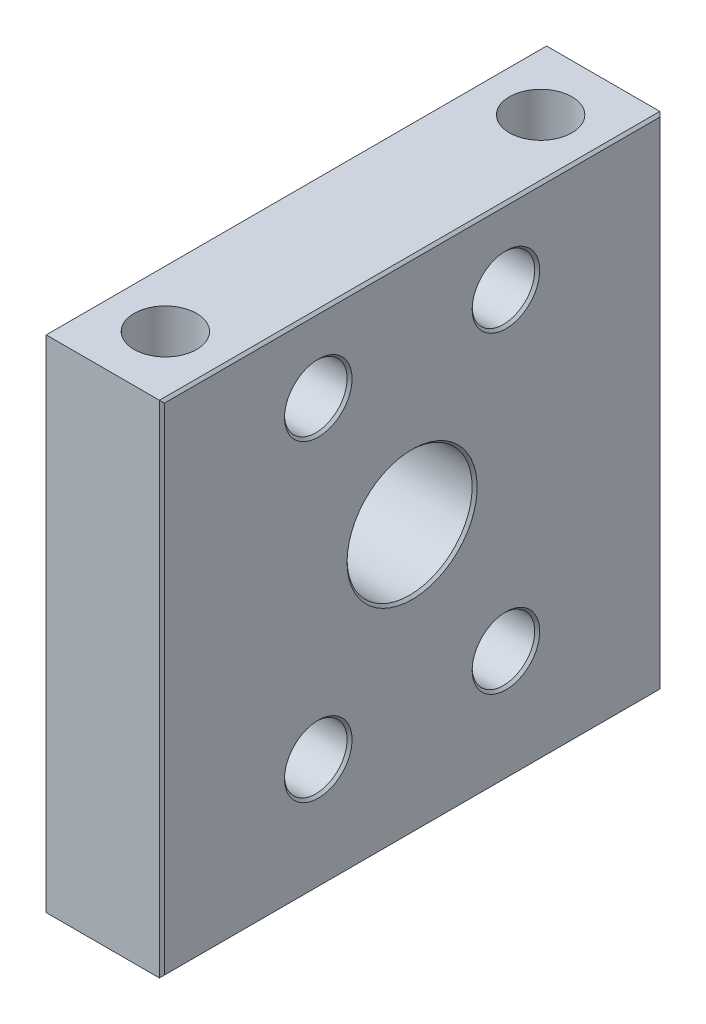
SolidWorks part; units mm, degrees
material "1060 Alloy"
ref_plane "Front Plane" through (0, 0, 0) normal (0, 0, 1) x (1, 0, 0)
ref_plane "Top Plane" through (0, 0, 0) normal (0, 1, 0) x (1, 0, 0)
ref_plane "Right Plane" through (0, 0, 0) normal (1, 0, 0) x (0, 0, -1)
sketch "Sketch1" plane through (0, 0, 0) normal (0, 1, 0) x (1, 0, 0)
  line L1 (6.001, -25.4) -> (-6.001, -25.4)
  line L2 (6.001, -25.4) -> (6.001, 25.4)
  line L3 (6.001, 25.4) -> (-6.001, 25.4)
  line L4 (-6.001, -25.4) -> (-6.001, 25.4)
  line L5 (6.001, -25.4) -> (-6.001, 25.4) construction
  line L6 (6.001, 25.4) -> (-6.001, -25.4) construction
  circle A0 centre (0, 19.05) radius 3.175
  circle A1 centre (0, -19.05) radius 3.175
  point P0 (0, 0)
  dimension "D1" = 6.35
  dimension "D3" = 6.35
  dimension "D2" = 50.8
  dimension "D4" = 38.1
  dimension "D5" = 6.35
extrude "Boss-Extrude1" add sketch "Sketch1" along normal blind 50.8
sketch "Sketch2" plane through (6.001, 0, 0) normal (1, 0, 0) x (0, 0, -1)
  line L15 (-9.525, 43.18) -> (9.525, 43.18) construction
  line L16 (9.525, 43.18) -> (9.525, 11.43) construction
  line L17 (9.525, 11.43) -> (-9.525, 11.43) construction
  line L18 (-9.525, 11.43) -> (-9.525, 43.18) construction
  line L19 (-25.4, 50.8) -> (25.4, 50.8) construction
  line L20 (-9.525, 43.18) -> (9.525, 11.43) construction
  line L21 (9.525, 43.18) -> (-9.525, 11.43) construction
  circle A0 centre (-9.525, 43.18) radius 3.175
  circle A1 centre (9.525, 43.18) radius 3.175
  circle A2 centre (0, 27.305) radius 6.35
  circle A3 centre (-9.525, 11.43) radius 3.175
  circle A4 centre (9.525, 11.43) radius 3.175
  point P14 (0, 27.305)
  point P15 (0, 50.8)
  point P16 (0, 43.18)
  dimension "D1" = 6.35
  dimension "D2" = 12.7
  dimension "D3" = 19.05
  dimension "D4" = 7.62
  dimension "D5" = 31.75
extrude "Cut-Extrude1" cut sketch "Sketch2" against normal blind 50.8
chamfer "Chamfer1" distance 0.254 angle 45 18 edges at (-6.001, 25.4, -25.4) (-6.001, 50.8, 0) (-6.001, 25.4, 25.4) (-6.001, 0, 0) (-6.001, 43.18, 6.35) (-6.001, 43.18, -12.7) (-6.001, 27.305, -6.35) (-6.001, 11.43, 6.35) (-6.001, 11.43, -12.7) (6.001, 25.4, 25.4) (6.001, 50.8, 0) (6.001, 25.4, -25.4) (6.001, 0, 0) (6.001, 43.18, 6.35) (6.001, 43.18, -12.7) (6.001, 27.305, -6.35) (6.001, 11.43, 6.35) (6.001, 11.43, -12.7)
